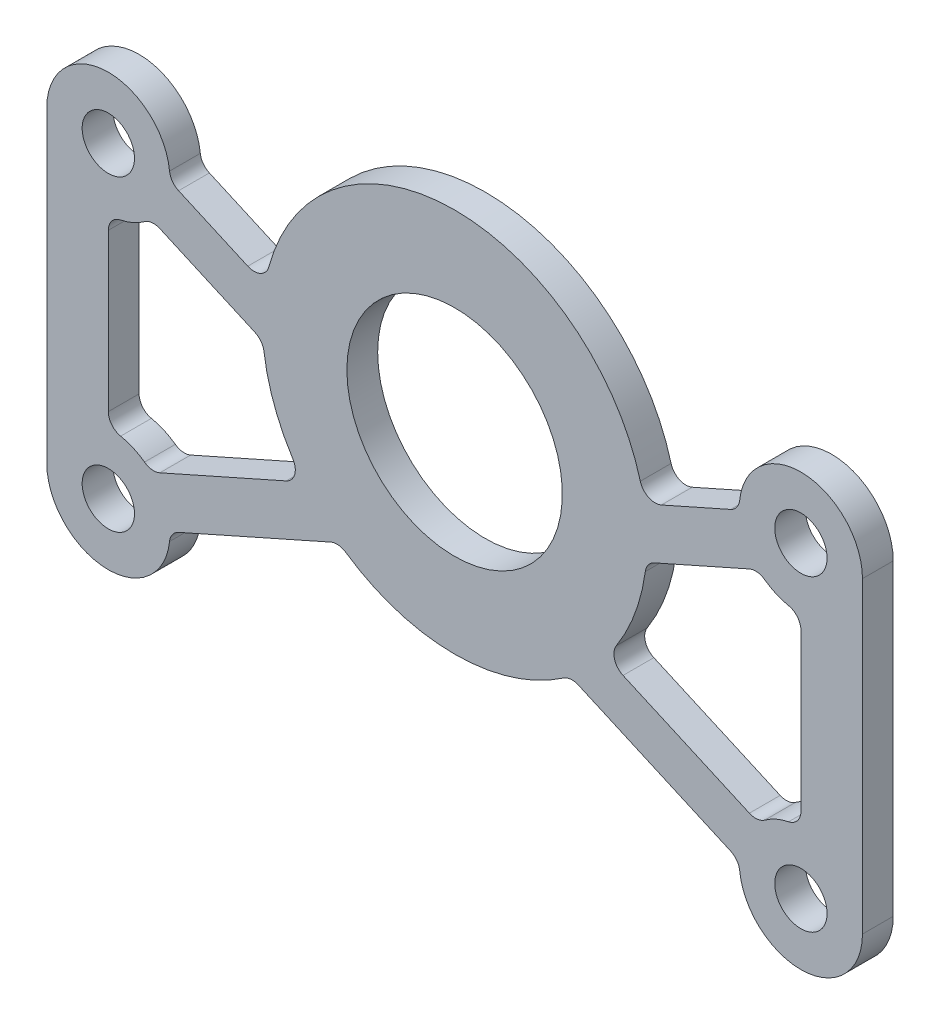
SolidWorks part; units mm, degrees
material "A2017"
ref_plane "正面" through (0, 0, 0) normal (0, 0, 1) x (1, 0, 0)
ref_plane "平面" through (0, 0, 0) normal (0, 1, 0) x (1, 0, 0)
ref_plane "右側面" through (0, 0, 0) normal (1, 0, 0) x (0, 0, -1)
sketch "ｽｹｯﾁ1" plane through (0, 0, 0) normal (0, 0, 1) x (1, 0, 0)
  circle A0 centre (0, 0) radius 12.5
  circle A1 centre (-22.5, 5) radius 4
  circle A2 centre (-22.5, -15) radius 4
  circle A3 centre (22.5, -15) radius 4
  circle A4 centre (22.5, 5) radius 4
  arc A5 (-26.1198, -13.2978) -> (-26.5, -15.0192) centre (-22.5, -15) ccw construction
  arc A6 (-26.3403, 6.1191) -> (-23.3, 1.0808) centre (-22.5, 5) ccw construction
  dimension "D1" = 25
extrude "ﾎﾞｽ - 押し出し1" add sketch "ｽｹｯﾁ1" along normal blind 2
sketch "ｽｹｯﾁ2" plane through (0, 0, 2) normal (0, 0, 1) x (1, 0, 0)
  line L1 (-22.5, -15) -> (-26.5, -15)
  line L2 (-22.5, -15) -> (-22.5, 5)
  line L3 (-22.5, 5) -> (-26.5, 5)
  line L4 (-26.5, -15) -> (-26.5, 5)
  line L5 (26.5, -15) -> (22.5, -15)
  line L6 (26.5, -15) -> (26.5, 5)
  line L7 (26.5, 5) -> (22.5, 5)
  line L8 (22.5, -15) -> (22.5, 5)
  circle A0 centre (-22.5, 5) radius 4 construction
  circle A1 centre (22.5, -15) radius 4 construction
  circle A3 centre (22.5, 5) radius 4 construction
  circle A4 centre (-22.5, -15) radius 4 construction
  circle A5 centre (22.5, -15) radius 4
  circle A6 centre (22.5, 5) radius 4
  circle A7 centre (-22.5, 5) radius 4
  circle A8 centre (-22.5, -15) radius 4
extrude "ﾎﾞｽ - 押し出し2" add sketch "ｽｹｯﾁ2" against normal up to surface (2 mm away) up to face at (12.5, 0, 0)
sketch "ｽｹｯﾁ3" plane through (0, 0, 2) normal (0, 0, 1) x (1, 0, 0)
  line L0 (-22.5, 5) -> (22.5, -15) construction
  line L1 (-21.8908, 6.3707) -> (23.1092, -13.6293)
  line L2 (-23.1092, 3.6293) -> (21.8908, -16.3707)
  line L3 (-22.5, -15) -> (22.5, 5) construction
  line L4 (-23.1092, -13.6293) -> (21.8908, 6.3707)
  line L5 (-21.8908, -16.3707) -> (23.1092, 3.6293)
  line L6 (-17.9339, -14.6121) -> (-5.2366, -8.9688) construction
  arc A0 (-21.8908, 6.3707) -> (-23.1092, 3.6293) centre (-22.5, 5) ccw
  arc A1 (21.8908, -16.3707) -> (23.1092, -13.6293) centre (22.5, -15) ccw
  arc A2 (-23.1092, -13.6293) -> (-21.8908, -16.3707) centre (-22.5, -15) ccw
  arc A3 (23.1092, 3.6293) -> (21.8908, 6.3707) centre (22.5, 5) ccw
  circle A5 centre (0, 0) radius 12.5
  circle A6 centre (0, 0) radius 12.5
  point P4 (0, -5)
  point P9 (0, -5)
  circle M3 centre (0, 0) radius 12.5
  dimension "D1" = 0
extrude "ﾎﾞｽ - 押し出し3" add sketch "ｽｹｯﾁ3" against normal through all contours L4 A2 L5 M3 | L2 A1 L1 M3 | L1 A0 L2 M3 | L5 A3 L4 M3
fillet "ﾌｨﾚｯﾄ1" radius 1 20 edges at (-18.5023, -14.8647, 1) (12.4508, -1.1078, 1) (-7.5211, -9.9842, 1) (7.5211, -9.9842, 1) (-12.4508, -1.1078, 1) (18.5023, -14.8647, 1) (12.3195, 2.1168, 1) (-9.8265, -7.7259, 1) (-19.7207, -12.1233, 1) (-22.5, -11, 1) (-22.5, 1, 1) (-19.7207, 2.1233, 1) (22.5, 1, 1) (22.5, -11, 1) (19.7207, -12.1233, 1) (9.8265, -7.7259, 1) (-12.3195, 2.1168, 1) (19.7207, 2.1233, 1) (18.5023, 4.8647, 1) (-18.5023, 4.8647, 1)
sketch "ｽｹｯﾁ5" plane through (0, 0, 0) normal (0, 0, -1) x (-1, 0, 0)
  circle A1 centre (0, 0) radius 7
  dimension "D1" = 14
extrude "ｶｯﾄ - 押し出し1" cut sketch "ｽｹｯﾁ5" against normal through all
hole_wizard "M3 すきま穴1" positions "ｽｹｯﾁ10" profile "ｽｹｯﾁ11" hole size "M3" standard "JIS" end condition through all
sketch "ｽｹｯﾁ10" plane through (0, 0, 2) normal (0, 0, 1) x (1, 0, 0)
  point P0 (-22.5, 5)
  point P3 (-22.5, -15)
  point P6 (22.5, -15)
  point P9 (22.5, 5)
sketch "ｽｹｯﾁ11" plane through (-22.5, 5, 2) normal (1, 0, 0) x (0, -1, 0)
  line L0 (0, 0) -> (0, 2)
  line L1 (0, 2) -> (1.7, 2)
  line L2 (1.7, 2) -> (1.7, 0)
  line L5 (1.7, 0) -> (0, 0)
  line L11 (0, -6.35) -> (0, 107.95) construction
  dimension "通し穴の直径" = 3.4
  dimension "通し穴の深さ" = 2
